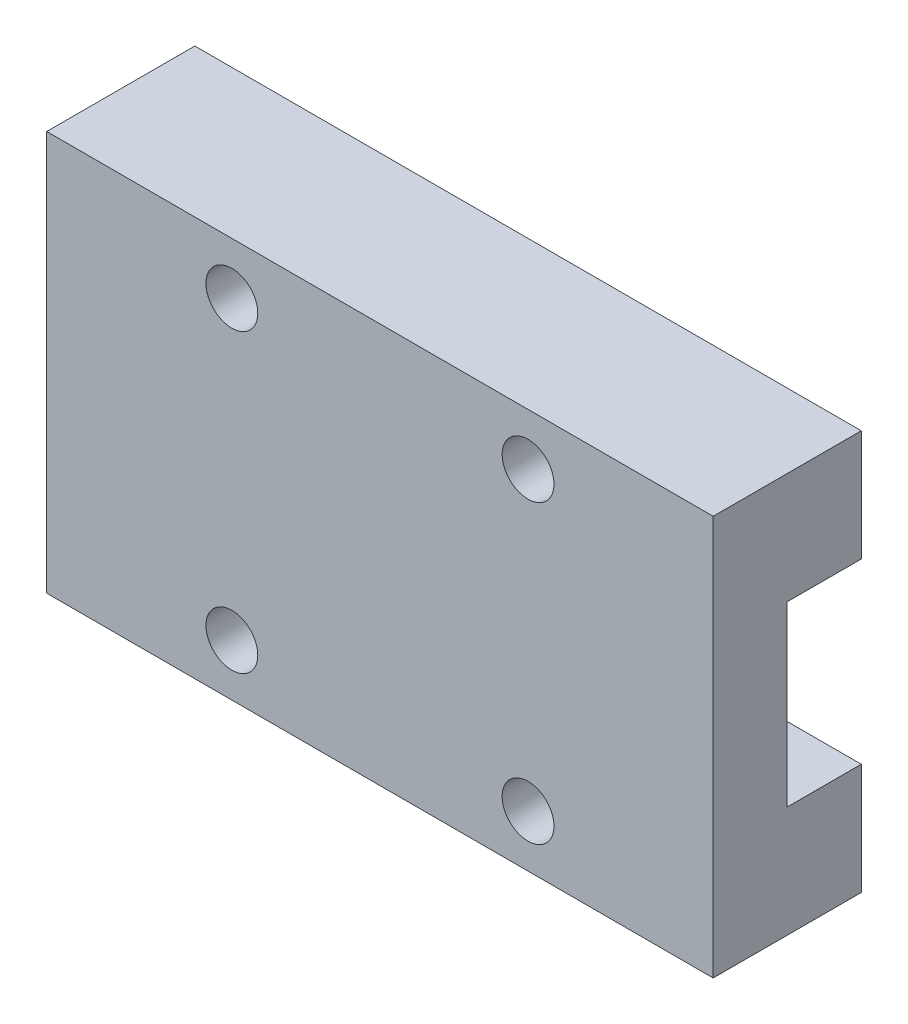
SolidWorks part; units mm, degrees
ref_plane "Top Plane" through (0, 0, 0) normal (0, 0, 1) x (1, 0, 0)
ref_plane "Right Plane" through (0, 0, 0) normal (0, 1, 0) x (1, 0, 0)
ref_plane "Front Plane" through (0, 0, 0) normal (1, 0, 0) x (0, 0, -1)
sketch "Sketch1" plane through (0, 0, 0) normal (1, 0, 0) x (0, 0, -1)
  line L0 (5, -6) -> (5, -13.5)
  line L1 (-5, 13.5) -> (5, 13.5)
  line L2 (-5, 13.5) -> (-5, -13.5)
  line L3 (-5, -13.5) -> (5, -13.5)
  line L4 (5, 13.5) -> (5, 6)
  line L5 (-5, 13.5) -> (5, -13.5) construction
  line L6 (-5, -13.5) -> (5, 13.5) construction
  line L7 (0, 6) -> (5, 6)
  line L8 (0, 6) -> (0, -6)
  line L9 (0, -6) -> (5, -6)
  point P4 (0, 0)
  point P5 (0, 0)
  dimension "D1" = 27
  dimension "D2" = 10
  dimension "D3" = 12
extrude "Boss-Extrude1" add sketch "Sketch1" along normal mid plane 45
sketch "Sketch3" plane through (0, 0, 5) normal (0, 0, 1) x (1, 0, 0)
  circle A0 centre (-10, 10) radius 1.75
  point P2 (0, 0)
  point P5 (-2.2295, -3.5986)
  dimension "D3" = 3.5
  dimension "D1" = 10
  dimension "D2" = 10
extrude "Cut-Extrude1" cut sketch "Sketch3" against normal blind 8
mirror "Mirror2" about plane through (0, 0, 0) normal (0, 1, 0) of "Cut-Extrude1"
mirror "Mirror3" about plane through (0, 0, 0) normal (1, 0, 0) of "Mirror2", "Cut-Extrude1"
